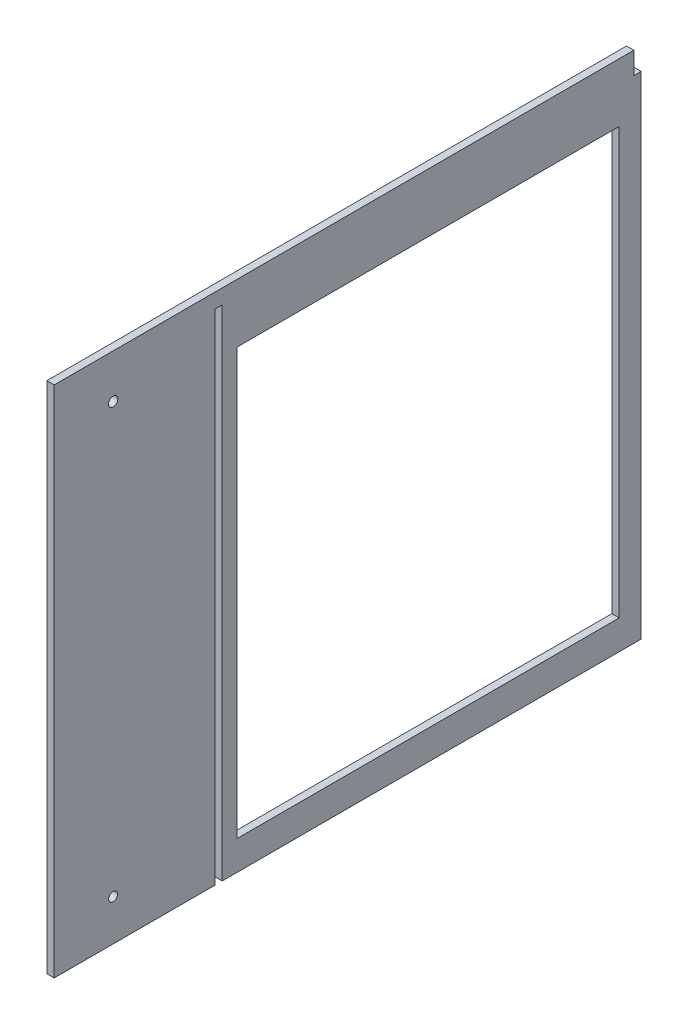
SolidWorks part; units mm, degrees
ref_plane "Alzado" through (0, 0, 0) normal (0, 0, 1) x (1, 0, 0)
ref_plane "Planta" through (0, 0, 0) normal (0, 1, 0) x (1, 0, 0)
ref_plane "Vista lateral" through (0, 0, 0) normal (1, 0, 0) x (0, 0, -1)
sketch "Croquis1" plane through (0, 0, 0) normal (0, 0, 1) x (1, 0, 0)
  line L1 (-331.2347, 90.0398) -> (-326.2347, 90.0398)
  line L2 (-331.2347, 90.0398) -> (-331.2347, -259.9602)
  line L3 (-331.2347, -259.9602) -> (-326.2347, -259.9602)
  line L4 (-326.2347, 90.0398) -> (-326.2347, -259.9602)
  dimension "D1" = 350
  dimension "D2" = 5
extrude "Saliente-Extruir1" add sketch "Croquis1" against normal blind 400
sketch "Croquis2" plane through (-331.2347, 0, 0) normal (-1, 0, 0) x (0, 0, 1)
  line L0 (-400, -259.9602) -> (0, -259.9602) construction
  line L1 (-109.5, -259.9602) -> (-114.5, -259.9602)
  line L2 (-109.5, -259.9602) -> (-109.5, 80.0398)
  line L3 (-109.5, 80.0398) -> (-114.5, 80.0398)
  line L4 (-114.5, -259.9602) -> (-114.5, 80.0398)
  line L5 (0, 90.0398) -> (0, -259.9602) construction
  line L6 (-400, 90.0398) -> (-400, -259.9602) construction
  line L7 (-124.5, -239.9602) -> (-385, -239.9602)
  line L8 (-124.5, -239.9602) -> (-124.5, 50.0398)
  line L9 (-124.5, 50.0398) -> (-385, 50.0398)
  line L10 (-385, -239.9602) -> (-385, 50.0398)
  line L11 (-400, 90.0398) -> (0, 90.0398) construction
  line L44 (-400, 90.0398) -> (-395, 90.0398)
  line L45 (-400, 90.0398) -> (-400, 75.0398)
  line L46 (-400, 75.0398) -> (-395, 75.0398)
  line L47 (-395, 90.0398) -> (-395, 75.0398)
  dimension "D1" = 5
  dimension "D2" = 109.5
  dimension "D3" = 15
  dimension "D4" = 40
  dimension "D5" = 10
  dimension "D6" = 20
  dimension "D15" = 10
  dimension "D16" = 5
  dimension "D17" = 15
extrude "Cortar-Extruir1" cut sketch "Croquis2" against normal blind 30
sketch "Croquis3" plane through (-331.2347, 0, 0) normal (-1, 0, 0) x (0, 0, 1)
  line L1 (-109.5, -259.9602) -> (0, -259.9602) construction
  circle A0 centre (-40.1848, 60.1747) radius 3.175
  circle A1 centre (-40.1848, -232.0102) radius 3.05
  dimension "D1" = 6.35
  dimension "D2" = 27.95
  dimension "D3" = 6.1
extrude "Cortar-Extruir2" cut sketch "Croquis3" against normal blind 10
